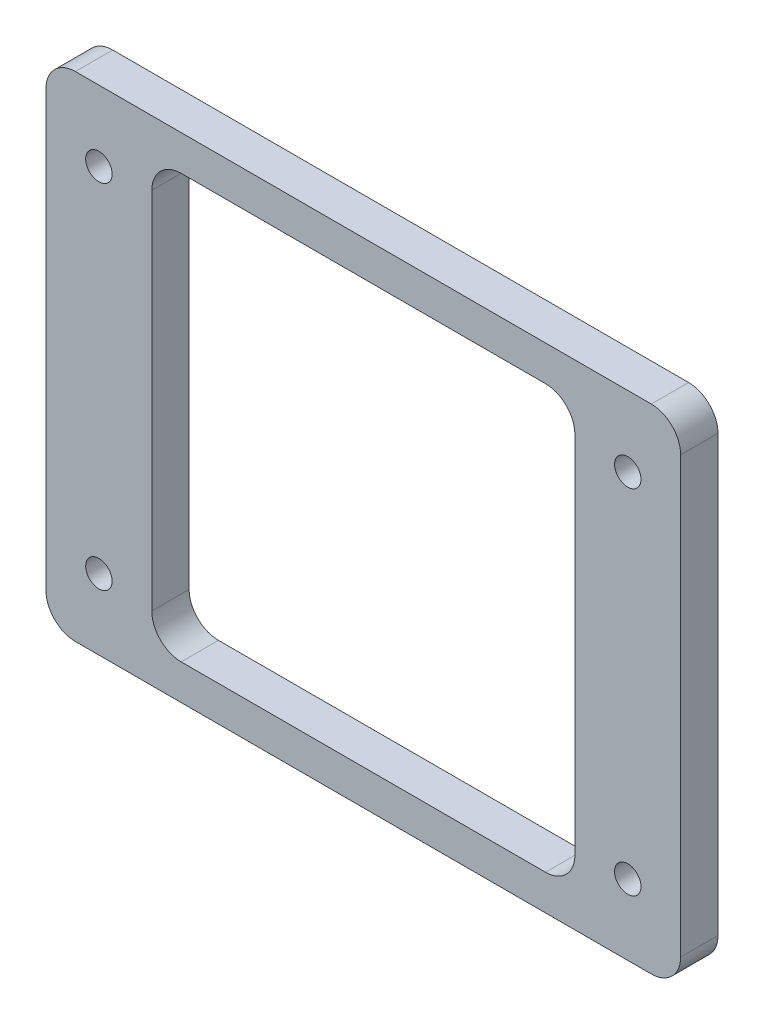
SolidWorks part; units mm, degrees
ref_plane "Front Plane" through (0, 0, 0) normal (0, 0, 1) x (1, 0, 0)
ref_plane "Top Plane" through (0, 0, 0) normal (0, 1, 0) x (1, 0, 0)
ref_plane "Right Plane" through (0, 0, 0) normal (1, 0, 0) x (0, 0, -1)
sketch "Sketch1" plane through (0, 0, 0) normal (0, 0, 1) x (1, 0, 0)
  line L0 (0.1076, 0) -> (-44.8924, 0) construction
  line L1 (-44.8924, 0) -> (-44.8924, 30) construction
  line L3 (45.1076, -30) -> (-44.8924, -30) construction
  line L4 (45.1076, -30) -> (45.1076, 30) construction
  line L5 (45.1076, 30) -> (-44.8924, 30) construction
  line L6 (-44.8924, -30) -> (-44.8924, 30) construction
  line L7 (45.1076, -30) -> (-44.8924, 30) construction
  line L8 (45.1076, 30) -> (-44.8924, -30) construction
  line L9 (54.1076, -42) -> (-53.8924, -42)
  line L10 (54.1076, -42) -> (54.1076, 42)
  line L11 (54.1076, 42) -> (-53.8924, 42)
  line L12 (-53.8924, -42) -> (-53.8924, 42)
  line L13 (54.1076, -42) -> (-53.8924, 42) construction
  line L14 (54.1076, 42) -> (-53.8924, -42) construction
  line L15 (36.1076, -36) -> (-35.8924, -36)
  line L16 (36.1076, -36) -> (36.1076, 36)
  line L17 (36.1076, 36) -> (-35.8924, 36)
  line L18 (-35.8924, -36) -> (-35.8924, 36)
  line L19 (36.1076, -36) -> (-35.8924, 36) construction
  line L20 (36.1076, 36) -> (-35.8924, -36) construction
  circle A0 centre (-44.8924, 30) radius 2.25
  circle A1 centre (45.1076, 30) radius 2.25
  circle A2 centre (45.1076, -30) radius 2.25
  circle A3 centre (-44.8924, -30) radius 2.25
  dimension "D3" = 2
  dimension "D1" = 30
  dimension "D2" = 45
  dimension "D5" = 9
  dimension "D6" = 12
  dimension "D7" = 72
  dimension "D8" = 72
  dimension "D4" = 2
extrude "Boss-Extrude1" add sketch "Sketch1" along normal blind 6.35
fillet "Fillet1" radius 5 8 edges at (54.1076, 42, 3.175) (54.1076, -42, 3.175) (-53.8924, -42, 3.175) (-53.8924, 42, 3.175) (36.1076, -36, 3.175) (-35.8924, -36, 3.175) (-35.8924, 36, 3.175) (36.1076, 36, 3.175)
